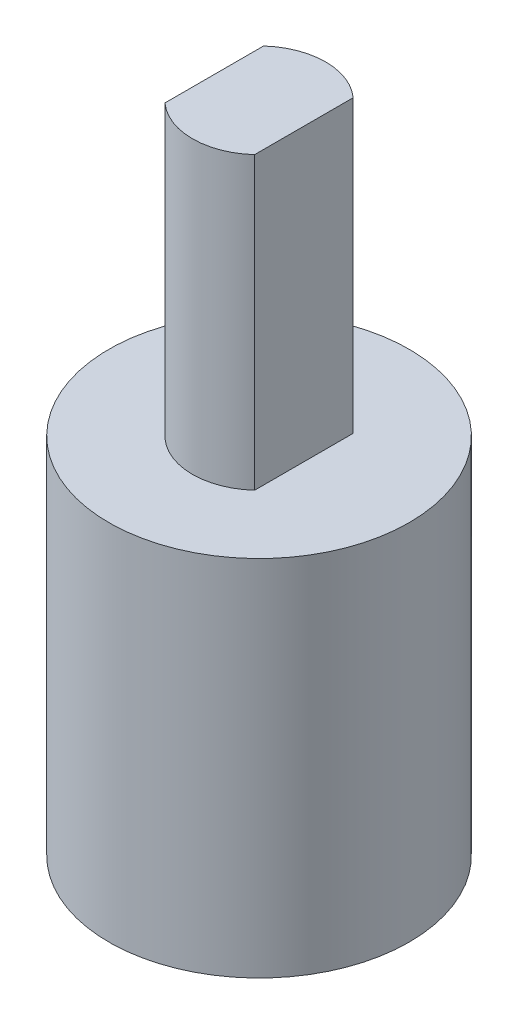
SolidWorks part; units mm, degrees
ref_plane "Alzado" through (0, 0, 0) normal (0, 0, 1) x (1, 0, 0)
ref_plane "Planta" through (0, 0, 0) normal (0, 1, 0) x (1, 0, 0)
ref_plane "Vista lateral" through (0, 0, 0) normal (1, 0, 0) x (0, 0, -1)
sketch "Croquis3" plane through (0, 0, 0) normal (0, 0, 1) x (1, 0, 0)
  line L0 (0, -169.6323) -> (0, 8311.9833) construction
  line L1 (3.2, 0) -> (6.2, 0)
  line L2 (3.2, 0) -> (3.2, 13)
  line L3 (3.2, 13) -> (0, 13)
  line L4 (0, 13) -> (0, 27)
  line L5 (0, 27) -> (2.75, 27)
  line L7 (6.2, 0) -> (6.2, 15)
  line L8 (6.2, 15) -> (2.75, 15)
  line L9 (2.75, 15) -> (2.75, 27)
  dimension "D1" = 6.4
  dimension "D2" = 13
  dimension "D3" = 12
  dimension "D4" = 3
  dimension "D5" = 2
  dimension "D6" = 5.5
revolve "Revolución1" add sketch "Croquis3" angle 360 about L0
sketch "Croquis4" plane through (0, 15, 0) normal (0, 1, 0) x (1, 0, 0)
  line L0 (0, -1000) -> (0, 49000) construction
  line L2 (1.85, 2.0347) -> (1.85, -2.0347)
  line L3 (-1.85, 2.0347) -> (-1.85, -2.0347)
  circle A0 centre (0, 0) radius 2.75 construction
  circle A1 centre (0, 0) radius 2.75 construction
  arc A2 (-1.85, 2.0347) -> (-1.85, -2.0347) centre (0, 0) ccw
  arc A3 (1.85, -2.0347) -> (1.85, 2.0347) centre (0, 0) ccw
  dimension "D1" = 3.7
extrude "Cortar-Extruir1" cut sketch "Croquis4" along normal through all
